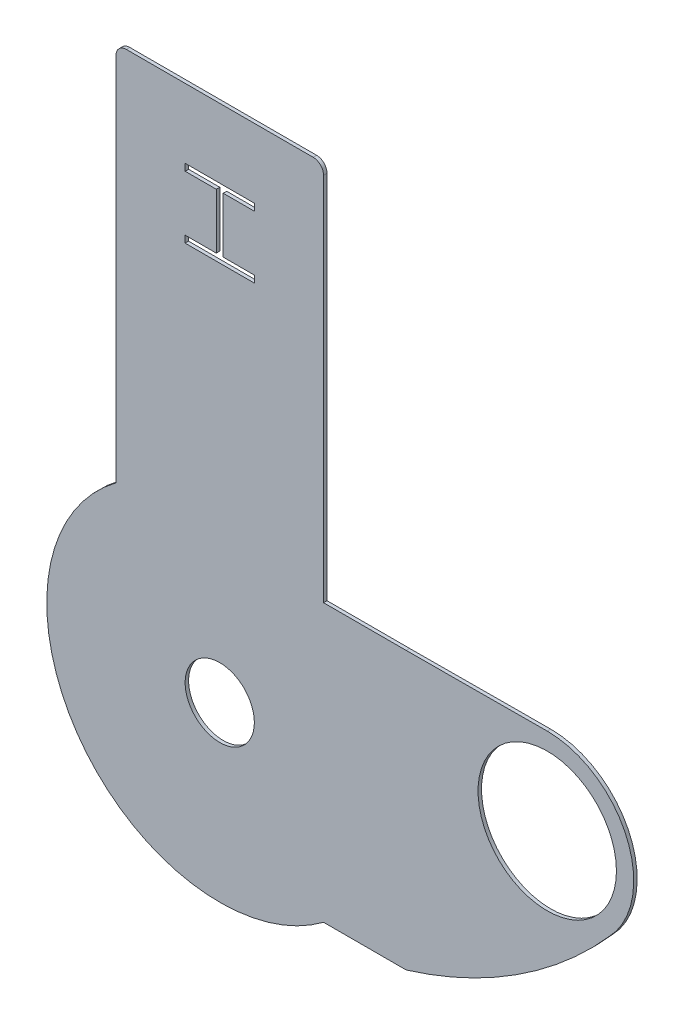
SolidWorks part; units mm, degrees
ref_plane "前视基准面" through (0, 0, 0) normal (0, 0, 1) x (1, 0, 0)
ref_plane "上视基准面" through (0, 0, 0) normal (0, 1, 0) x (1, 0, 0)
ref_plane "右视基准面" through (0, 0, 0) normal (1, 0, 0) x (0, 0, -1)
sketch "Sketch1" plane through (0, 0, 0) normal (0, 0, 1) x (1, 0, 0)
  line L0 (53.885, 40) -> (94.66, 40.19)
  line L1 (53.885, -40) -> (-53.885, -40)
  line L3 (53.885, 40) -> (-53.885, 40)
  line L4 (-53.885, -40) -> (-53.885, 40)
  line L5 (53.885, -40) -> (-53.885, 40) construction
  line L6 (53.885, 40) -> (-53.885, -40) construction
  arc A0 (112.5941, -2.2275) -> (94.427, 40.1889) centre (94.66, 15.19) ccw
  circle A1 centre (91.76, 19.26) radius 10
  arc A2 (112.5941, -2.2275) -> (53.885, -40) centre (16.4179, 82.7459) cw
  point P0 (0, 0)
  dimension "D5" = 50
  dimension "D6" = 20
  dimension "D1" = 80
  dimension "D2" = 107.77
  dimension "D3" = 94.66
  dimension "D4" = 15.19
  dimension "D7" = 91.76
  dimension "D8" = 19.26
extrude "Boss-Extrude1" add sketch "Sketch1" along normal blind 1 contours A2 A0 L0 L3 L4 L1 A1
sketch "Sketch2" plane through (0, 0, 1) normal (0, 0, 1) x (1, 0, 0)
  circle A0 centre (0, 0) radius 10
  dimension "D1" = 20
extrude "Cut-Extrude1" cut sketch "Sketch2" against normal blind 1
sketch "Sketch3" plane through (0, 0, 1) normal (0, 0, 1) x (1, 0, 0)
  circle A0 centre (94.66, 15.19) radius 20
  dimension "D3" = 40
  dimension "D1" = 94.66
  dimension "D2" = 15.19
extrude "Cut-Extrude2" cut sketch "Sketch3" against normal blind 1
sketch "Sketch4" plane through (0, 0, 1) normal (0, 0, 1) x (1, 0, 0)
  line L0 (-53.885, 40) -> (-30, 40)
  line L1 (53.885, 40) -> (-53.885, 40) construction
  line L2 (-53.885, 40) -> (-53.885, -40)
  line L3 (-30, -40) -> (-53.885, -40)
  arc A0 (-30, 40) -> (-30, -40) centre (0, 0) ccw
extrude "Cut-Extrude3" cut sketch "Sketch4" against normal through all
sketch "Sketch5" plane through (0, 0, 1) normal (0, 0, 1) x (1, 0, 0)
  line L2 (-30, -40) -> (30, -40)
  line L3 (53.885, -40) -> (-30, -40) construction
  arc A1 (-30, -40) -> (30, -40) centre (0, 0) ccw
extrude "Boss-Extrude2" add sketch "Sketch5" against normal blind 1
sketch "Sketch6" plane through (0, 0, 1) normal (0, 0, 1) x (1, 0, 0)
  line L0 (-30, 40) -> (-30, 147)
  line L1 (0, 49.5734) -> (0, 131.4724) construction
  line L2 (-27, 150) -> (27, 150)
  line L3 (30, 40) -> (30, 147)
  line L4 (-30, 40) -> (30, 40)
  line L9 (-7.5, 130) -> (1, 118.6667) construction
  line L10 (-7.5, 110) -> (-6, 112) construction
  line L11 (13.1772, 120) -> (-9.4157, 120) construction
  line L12 (-1, 128) -> (-1, 112)
  line L13 (-1, 112) -> (-10, 112)
  line L14 (-10, 112) -> (-10, 110)
  line L15 (-10, 110) -> (10, 110)
  line L16 (-10, 130) -> (10, 130)
  line L17 (-10, 128) -> (-10, 130)
  line L18 (-1, 128) -> (-10, 128)
  line L19 (10, 112) -> (10, 110)
  line L20 (1, 112) -> (10, 112)
  line L21 (1, 128) -> (1, 112)
  line L22 (1, 128) -> (10, 128)
  line L23 (10, 128) -> (10, 130)
  line L24 (6, 112) -> (7.5, 110) construction
  line L25 (-1, 118.6667) -> (7.5, 130) construction
  arc A0 (-30, 147) -> (-27, 150) centre (-27, 147) cw
  arc A1 (30, 147) -> (27, 150) centre (27, 147) ccw
  point P6 (0, 120)
  point P9 (0, 150)
  point P25 (-1, 120)
  point P26 (0, 110)
  point P31 (0, 130)
  point P37 (-30, 150)
  point P40 (30, 150)
  dimension "D2" = 3
  dimension "D1" = 150
  dimension "D4" = 120
  dimension "D5" = 10
  dimension "D6" = 2
  dimension "D7" = 10
  dimension "D8" = 1
extrude "Boss-Extrude4" add sketch "Sketch6" against normal blind 1
